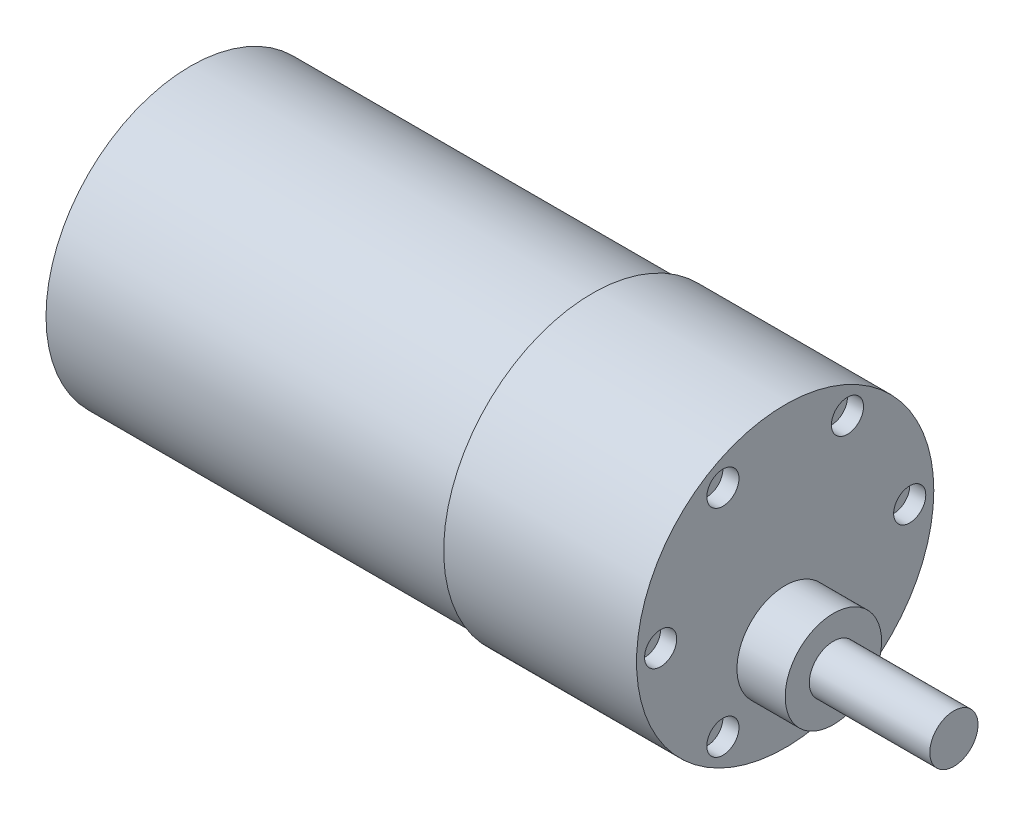
SolidWorks part; units mm, degrees
ref_plane "Front Plane" through (0, 0, 0) normal (0, 0, 1) x (1, 0, 0)
ref_plane "Top Plane" through (0, 0, 0) normal (0, 1, 0) x (1, 0, 0)
ref_plane "Right Plane" through (0, 0, 0) normal (1, 0, 0) x (0, 0, -1)
sketch "Sketch1" plane through (0, 0, 0) normal (1, 0, 0) x (0, 0, -1)
  circle A0 centre (0, 0) radius 18.5
  circle A1 centre (0, -7) radius 6 construction
  circle A2 centre (-15.5, 0) radius 2 construction
  circle A3 centre (-7.75, 13.4234) radius 2 construction
  circle A4 centre (7.75, 13.4234) radius 2 construction
  circle A5 centre (15.5, 0) radius 2 construction
  circle A6 centre (7.75, -13.4234) radius 2 construction
  circle A7 centre (-7.75, -13.4234) radius 2 construction
  point P19 (0, 0)
  dimension "D1" = 37
  dimension "D3" = 12
  dimension "D4" = 15.5
  dimension "D5" = 4
  dimension "D2" = 7
  dimension "D6" = 6
extrude "Boss-Extrude1" add sketch "Sketch1" against normal blind 24
sketch "Sketch2" plane through (-24, 0, 0) normal (-1, 0, 0) x (0, 0, 1)
  circle A0 centre (0, 0) radius 18
extrude "Boss-Extrude2" add sketch "Sketch2" along normal blind 50
sketch "Sketch3" plane through (0, 0, 0) normal (1, 0, 0) x (0, 0, -1)
  line L0 (0, 0) -> (0, -7) construction
  circle A1 centre (0, -7) radius 6
  dimension "D2" = 12
  dimension "D1" = 7
extrude "Boss-Extrude3" add sketch "Sketch3" along normal blind 6
sketch "Sketch4" plane through (6, 0, 0) normal (1, 0, 0) x (0, 0, -1)
  circle A0 centre (0, -7) radius 3
  dimension "D1" = 6
extrude "Boss-Extrude4" add sketch "Sketch4" along normal blind 15
sketch "Sketch5" plane through (0, 0, 0) normal (1, 0, 0) x (0, 0, -1)
  line L0 (-15.5, 0) -> (0, 0) construction
  circle A0 centre (-15.5, 0) radius 2
  circle A1 centre (-7.75, 13.4234) radius 2
  circle A2 centre (7.75, 13.4234) radius 2
  circle A3 centre (15.5, 0) radius 2
  circle A4 centre (7.75, -13.4234) radius 2
  circle A5 centre (-7.75, -13.4234) radius 2
  point P15 (0, 0)
  dimension "D2" = 4
  dimension "D1" = 15.5
  dimension "D3" = 6
extrude "Cut-Extrude1" cut sketch "Sketch5" against normal blind 2
